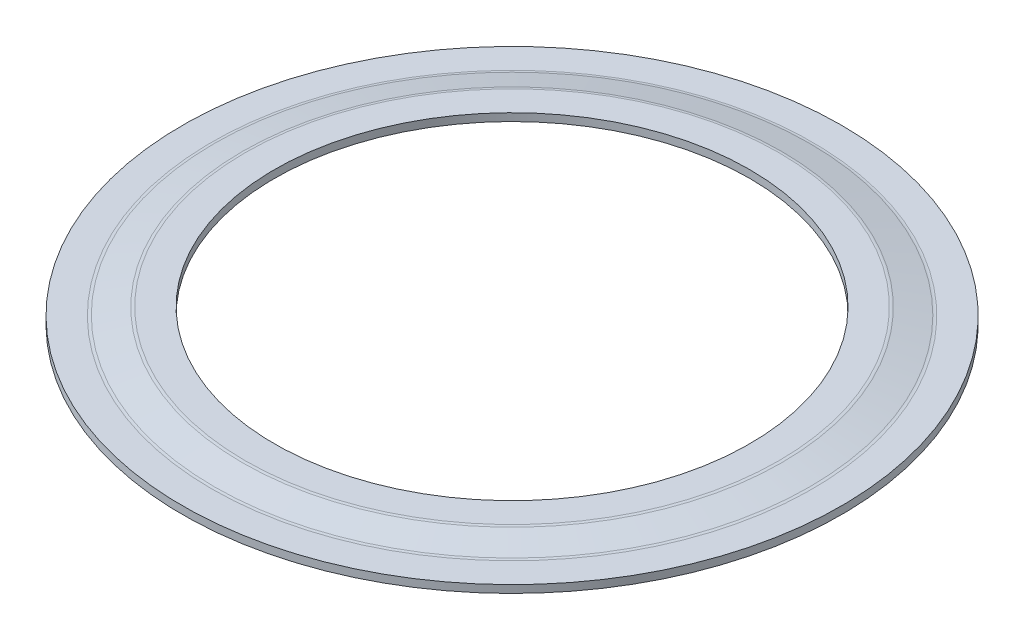
SolidWorks part; units mm, degrees
material "AISI 316 Stainless Steel Sheet (SS)"
ref_plane "Front Plane" through (0, 0, 0) normal (0, 0, 1) x (1, 0, 0)
ref_plane "Top Plane" through (0, 0, 0) normal (0, 1, 0) x (1, 0, 0)
ref_plane "Right Plane" through (0, 0, 0) normal (1, 0, 0) x (0, 0, -1)
sketch "Sketch1" plane through (0, 0, 0) normal (1, 0, 0) x (0, 0, -1)
  line L0 (0, 0) -> (0, 61.8307) construction
  line L1 (15.5, -0.5) -> (21.5, -0.5) construction
  line L2 (15.5, -0.5) -> (15.5, 0.5) construction
  line L3 (15.5, 0.5) -> (21.5, 0.5) construction
  line L4 (21.5, -0.5) -> (21.5, 0.5) construction
  line L5 (15.5, -0.5) -> (21.5, 0.5) construction
  line L6 (15.5, 0.5) -> (21.5, -0.5) construction
  line L7 (15.5, 0.5) -> (17.5, 0.5)
  line L8 (17.5, 0.5) -> (19.5, 0)
  line L9 (19.5, 0) -> (21.5, 0)
  line L10 (21.5, 0) -> (21.5, -0.5)
  line L11 (21.5, -0.5) -> (19.5, -0.5)
  line L12 (19.5, -0.5) -> (17.5, 0)
  line L13 (17.5, 0) -> (15.5, 0)
  line L14 (15.5, 0) -> (15.5, 0.5)
  point P0 (18.5, 0)
  point P12 (19.6438, 0)
  point P15 (0, 0)
  dimension "D1" = 15.5
  dimension "D2" = 21.5
  dimension "D3" = 1
  dimension "D4" = 2
revolve "Revolve1" add sketch "Sketch1" angle 360 about L0
fillet "Fillet1" radius 0.75 4 edges at (0, 0, -17.5) (0, -0.5, -19.5) (0, 0, -19.5) (0, 0.5, -17.5)
